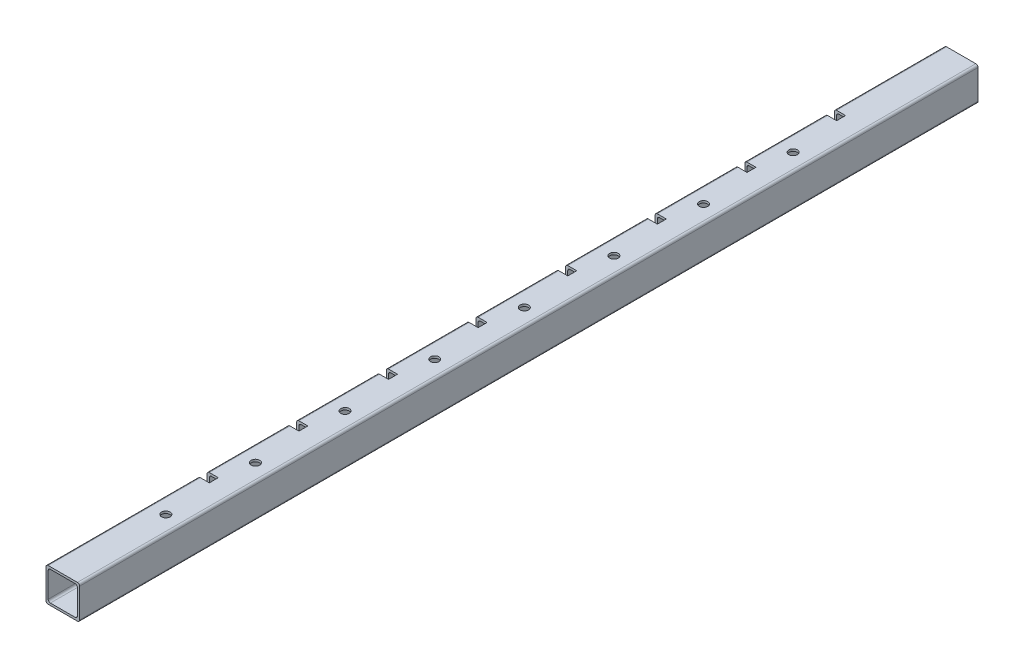
SolidWorks part; units mm, degrees
ref_plane "Front Plane" through (0, 0, 0) normal (0, 0, 1) x (1, 0, 0)
ref_plane "Top Plane" through (0, 0, 0) normal (0, 1, 0) x (1, 0, 0)
ref_plane "Right Plane" through (0, 0, 0) normal (1, 0, 0) x (0, 0, -1)
sketch "Sketch1" plane through (0, 0, 0) normal (0, 0, 1) x (1, 0, 0)
  line L0 (-9.525, 0) -> (9.525, 0) construction
  line L1 (0, -9.525) -> (0, 9.525) construction
  line L2 (8.2804, 0) -> (8.2804, 8.2804) construction
  line L3 (-9.525, -9.525) -> (9.525, -9.525) construction
  line L4 (-9.525, -9.525) -> (-9.525, 9.525) construction
  line L5 (-9.525, 9.525) -> (9.525, 9.525) construction
  line L6 (9.525, -9.525) -> (9.525, 9.525) construction
  line L7 (-9.525, -9.525) -> (9.525, 9.525) construction
  line L8 (-9.525, 9.525) -> (9.525, -9.525) construction
  line L9 (8.2804, 8.2804) -> (-8.2804, 8.2804) construction
  line L10 (-8.2804, 8.2804) -> (-8.2804, -8.2804) construction
  line L11 (-8.2804, -8.2804) -> (8.2804, -8.2804) construction
  line L12 (8.2804, -8.2804) -> (8.2804, 0) construction
  point P0 (0, 0)
  point P4 (0, 0)
  point P9 (0, 0)
  point P10 (8.2804, 0)
  point P13 (0, -8.2804)
  point P14 (-8.2804, 0)
  point P15 (0, 8.2804)
  dimension "Width" = 19.05
  dimension "Wall Thickness" = 1.2446
  dimension "Height" = 19.05
  dimension "D1" = 1.2446
  dimension "D2" = 1.2446
  dimension "D3" = 1.2446
sketch "Sketch2" plane through (0, 0, 0) normal (1, 0, 0) x (0, 0, -1)
  line L0 (254.635, 9.525) -> (-254.635, 9.525) construction
  point P3 (-232.7275, 9.525)
  point P5 (232.7275, 9.525)
  point P7 (0, 9.525)
  dimension "D1" = 21.9075
  dimension "D2" = 21.9075
  dimension "Length" = 509.27
sketch "Sketch3" plane through (0, 0, 0) normal (0, 0, 1) x (1, 0, 0)
  line L1 (9.525, 9.525) -> (-9.525, 9.525)
  line L2 (-9.525, 9.525) -> (-9.525, -9.525)
  line L3 (-9.525, -9.525) -> (9.525, -9.525) construction
  line L4 (-9.525, -9.525) -> (9.525, -9.525)
  line L5 (9.525, -9.525) -> (9.525, 9.525)
  line L6 (-8.2804, 8.2804) -> (8.2804, 8.2804)
  line L7 (8.2804, 8.2804) -> (8.2804, -8.2804)
  line L8 (8.2804, -8.2804) -> (-8.2804, -8.2804)
  line L9 (-8.2804, -8.2804) -> (-8.2804, 8.2804)
extrude "Boss-Extrude1" add sketch "Sketch3" along normal mid plane 509.27
fillet "Fillet1" radius 1.2446 8 edges at (-9.525, 9.525, 0) (8.2804, -8.2804, 0) (-8.2804, -8.2804, 0) (-8.2804, 8.2804, 0) (8.2804, 8.2804, 0) (9.525, -9.525, 0) (-9.525, -9.525, 0) (9.525, 9.525, 0)
sketch "Sketch4" plane through (0, 9.525, 0) normal (0, 1, 0) x (1, 0, 0)
  line L0 (0, 254.635) -> (0, 159.385) construction
  line L1 (8.2804, 254.635) -> (-8.2804, 254.635) construction
  line L2 (0, 159.385) -> (0, 108.585) construction
  circle A0 centre (0, 159.385) radius 2.413
  circle A1 centre (0, 108.585) radius 2.413
  circle A2 centre (0, 57.785) radius 2.413
  circle A3 centre (0, 6.985) radius 2.413
  circle A4 centre (0, -43.815) radius 2.413
  circle A5 centre (0, -94.615) radius 2.413
  circle A6 centre (0, -145.415) radius 2.413
  circle A7 centre (0, -196.215) radius 2.413
  dimension "D2" = 4.826
  dimension "D4" = 4.826
  dimension "D1" = 95.25
  dimension "D3" = 50.8
  dimension "D5" = 7
extrude "Cut-Extrude1" cut sketch "Sketch4" against normal up to next
sketch "Sketch6" plane through (-9.525, 0, 0) normal (-1, 0, 0) x (0, 0, 1)
  line L0 (-254.635, 0) -> (-179.705, 0) construction
  line L1 (-254.635, 8.2804) -> (-254.635, -8.2804) construction
  line L2 (-182.118, -1.651) -> (-187.198, -1.651)
  line L7 (-182.118, -6.477) -> (-177.292, -1.651) construction
  line L12 (-177.292, -6.477) -> (-182.118, -6.477)
  line L13 (-177.292, -6.477) -> (-177.292, -1.651)
  line L14 (-177.292, -1.651) -> (-182.118, -1.651)
  line L15 (-182.118, -6.477) -> (-182.118, -1.651) construction
  line L16 (-192.278, 9.525) -> (-192.278, -6.477)
  line L17 (-177.292, -6.477) -> (-182.118, -1.651) construction
  line L18 (-254.635, 9.525) -> (254.635, 9.525) construction
  line L19 (-192.278, -6.477) -> (-182.118, -6.477)
  line L20 (-187.198, -1.651) -> (-187.198, 9.525)
  line L21 (-187.198, 9.525) -> (-192.278, 9.525)
  point P12 (-179.705, -4.064)
  dimension "D1" = 74.93
  dimension "D2" = 16.002
  dimension "D3" = 4.826
  dimension "D4" = 4.826
  dimension "D5" = 10.16
  dimension "D6" = 5.08
extrude "Cut-Extrude3" cut sketch "Sketch6" against normal blind 6.35
pattern_linear "LPattern2" count 8 spacing 50.8 along (0, 0, 1) of "Cut-Extrude3"
equation "\"D1@Boss-Extrude1\" = \"Length@Sketch2\""
equation "\"D1@Sketch2\" = \"Width@Sketch1\" * 1.15"
equation "\"D2@Sketch2\"=\"D1@Sketch2\""
equation "\"D1@Sketch1\"=\"Wall Thickness@Sketch1\""
equation "\"D2@Sketch1\"=\"Wall Thickness@Sketch1\""
equation "\"D3@Sketch1\"=\"Wall Thickness@Sketch1\""
equation "\"D1@Fillet1\"=\"Wall Thickness@Sketch1\""
